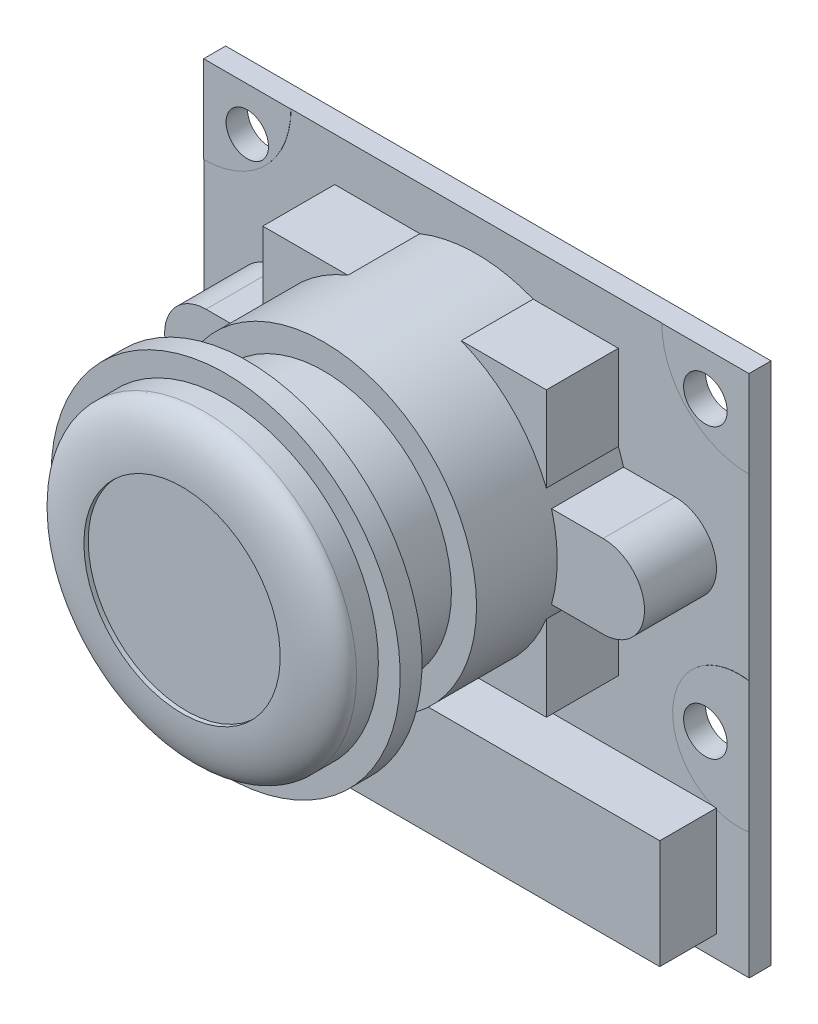
SolidWorks part; units mm, degrees
ref_plane "Alzado" through (0, 0, 0) normal (0, 0, 1) x (1, 0, 0)
ref_plane "Planta" through (0, 0, 0) normal (0, 1, 0) x (1, 0, 0)
ref_plane "Vista lateral" through (0, 0, 0) normal (1, 0, 0) x (0, 0, -1)
sketch "Croquis1" plane through (0, 0, 0) normal (0, 0, 1) x (1, 0, 0)
  line L1 (12.5, 12) -> (-12.5, 12)
  line L2 (12.5, 12) -> (12.5, -12)
  line L3 (12.5, -12) -> (-12.5, -12)
  line L4 (-12.5, 12) -> (-12.5, -12)
  line L5 (12.5, 12) -> (-12.5, -12) construction
  line L6 (12.5, -12) -> (-12.5, 12) construction
  point P0 (0, 0)
  dimension "D1" = 25
  dimension "D2" = 24
extrude "Saliente-Extruir1" add sketch "Croquis1" along normal blind 1
sketch "Croquis2" plane through (0, 0, 1) normal (0, 0, 1) x (1, 0, 0)
  line L0 (-12.5, -12) -> (12.5, -12) construction
  line L1 (11, -6) -> (-11, -6)
  line L2 (11, -6) -> (11, -11)
  line L3 (11, -11) -> (-11, -11)
  line L4 (-11, -6) -> (-11, -11)
  line L5 (11, -6) -> (-11, -11) construction
  line L6 (11, -11) -> (-11, -6) construction
  point P0 (0, -8.5)
  point P5 (0, 0)
  dimension "D1" = 22
  dimension "D2" = 5
  dimension "D3" = 1
extrude "Saliente-Extruir2" add sketch "Croquis2" along normal blind 2.6
sketch "Croquis3" plane through (0, 0, 1) normal (0, 0, 1) x (1, 0, 0)
  line L0 (-9.1, 5.4) -> (-6.5, 5.4)
  line L1 (-6.5, -3) -> (6.5, -3)
  line L2 (-6.5, -3) -> (-6.5, 1.6)
  line L3 (-6.5, 10) -> (6.5, 10)
  line L4 (6.5, -3) -> (6.5, 1.6)
  line L5 (-6.5, -3) -> (6.5, 10) construction
  line L6 (-6.5, 10) -> (6.5, -3) construction
  line L7 (-6.5, 5.4) -> (-6.5, 10)
  line L8 (6.5, 5.4) -> (9.1, 5.4)
  line L9 (6.5, 5.4) -> (6.5, 10)
  line L10 (9.1, 1.6) -> (6.5, 1.6)
  line L11 (12.5, 12) -> (-12.5, 12) construction
  line L12 (-6.5, 1.6) -> (-9.1, 1.6)
  arc A0 (-9.1, 5.4) -> (-9.1, 1.6) centre (-9.1, 3.5) ccw
  arc A1 (9.1, 1.6) -> (9.1, 5.4) centre (9.1, 3.5) ccw
  point P1 (0, 0)
  point P3 (-11, 3.5)
  point P4 (0, 3.5)
  point P9 (-7.6876, 4.6938)
  point P18 (-7.8, 1.6)
  point P19 (11, 3.5)
  point P20 (0, 0)
  dimension "D1" = 22
  dimension "D2" = 3.8
  dimension "D3" = 13
  dimension "D4" = 13
  dimension "D5" = 2
extrude "Saliente-Extruir3" add sketch "Croquis3" along normal blind 3.3
sketch "Croquis5" plane through (0, 0, 1) normal (0, 0, 1) x (1, 0, 0)
  line L0 (-11, 3.5) -> (11, 3.5) construction
  arc A0 (-9.1, 5.4) -> (-9.1, 1.6) centre (-9.1, 3.5) ccw construction
  arc A1 (9.1, 1.6) -> (9.1, 5.4) centre (9.1, 3.5) ccw construction
  circle A2 centre (0, 3.5) radius 7
  dimension "D1" = 14
extrude "Saliente-Extruir4" add sketch "Croquis5" along normal blind 7
sketch "Croquis6" plane through (0, 0, 8) normal (0, 0, 1) x (1, 0, 0)
  circle A0 centre (0, 3.5) radius 5.85
  dimension "D1" = 11.7
extrude "Saliente-Extruir5" add sketch "Croquis6" along normal blind 3.5
sketch "Croquis7" plane through (0, 0, 11.5) normal (0, 0, 1) x (1, 0, 0)
  point P0 (0, 3.5)
ref_plane "Plano1" through (0, 3.5, 0) normal (0, -1, 0) x (-1, 0, 0)
sketch "Croquis8" plane through (0, 3.5, 0) normal (0, -1, 0) x (-1, 0, 0)
  line L0 (0, -11.5) -> (-8, -11.5)
  line L1 (-5.85, -11.5) -> (5.85, -11.5) construction
  line L2 (-8, -11.5) -> (-8, -12.5)
  line L3 (-8, -12.5) -> (-7, -12.5)
  line L4 (-7, -12.5) -> (-7, -13.5)
  line L5 (0, -11.5) -> (0, -14.3)
  line L6 (-4.5, -14.5) -> (-4.5, -14.3)
  line L7 (-4.5, -14.3) -> (0, -14.3)
  ellipse E0 centre (-4.5, -13.5) end of major axis (-7, -13.5) minor radius 1 (-7, -13.5) -> (-4.5, -14.5) ccw
  point P9 (0, 0)
  point P12 (0, 0)
  point P13 (0, 0)
  dimension "D1" = 8
  dimension "D2" = 1
  dimension "D3" = 1
  dimension "D4" = 4.5
  dimension "D5" = 3
  dimension "D6" = 0.2
  dimension "D7" = 1
revolve "Revolución1" add sketch "Croquis8" angle 360 about L5
sketch "Croquis9" plane through (0, 0, 1) normal (0, 0, 1) x (1, 0, 0)
  line L0 (12.5, 12) -> (-12.5, 12) construction
  line L1 (-10.5, 10) -> (10.5, 10) construction
  line L2 (-10.5, 10) -> (-10.5, -3.2) construction
  line L3 (-10.5, -3.2) -> (10.5, -3.2) construction
  line L4 (10.5, 10) -> (10.5, -3.2) construction
  circle A4 centre (-10.5, 10) radius 1
  circle A5 centre (-10.5, -3.2) radius 1
  circle A6 centre (10.5, -3.2) radius 1
  circle A7 centre (10.5, 10) radius 1
  point P8 (0, 10)
  dimension "D1" = 2
  dimension "D2" = 13.2
  dimension "D3" = 21
  dimension "D4" = 2
extrude "Cortar-Extruir1" cut sketch "Croquis9" against normal up to surface (1 mm away) up to face at (0, 0, 0)
sketch "Croquis10" plane through (0, 0, 1) normal (0, 0, 1) x (1, 0, 0)
  line L0 (-12.0357, -3.2) -> (12.0357, -3.2) construction
  line L1 (-12.5, 8) -> (-12.5, 12)
  line L2 (-12.5, 12) -> (-8.5, 12)
  line L3 (-12.5, -0.2) -> (-12.5, -6.2)
  line L4 (8.5, 12) -> (12.5, 12)
  line L5 (12.5, 12) -> (12.5, 8)
  line L7 (12.5, -6.2) -> (12.5, -0.2)
  arc A0 (-12.5, 8) -> (-8.5, 12) centre (-12.5, 12) ccw
  arc A1 (8.5, 12) -> (12.5, 8) centre (12.5, 12) ccw
  arc A2 (12.5, -0.2) -> (12.5, -6.2) centre (12.0357, -3.2) ccw
  arc A3 (-12.5, -6.2) -> (-12.5, -0.2) centre (-12.0357, -3.2) ccw
  circle A4 centre (-10.5, 10) radius 0.9725
  circle A6 centre (10.5, -3.2) radius 1
  circle A7 centre (10.5, 10) radius 1
  circle A8 centre (-10.5, -3.2) radius 1
  circle A9 centre (-10.5, -3.2) radius 1 construction
  point P7 (-9, -3.2)
  point P10 (0, -3.2)
  point P11 (-10.5, -3.2)
  dimension "D1" = 4
  dimension "D2" = 3.5
  dimension "D3" = 6
extrude "Saliente-Extruir6" add sketch "Croquis10" along normal blind 0.01
